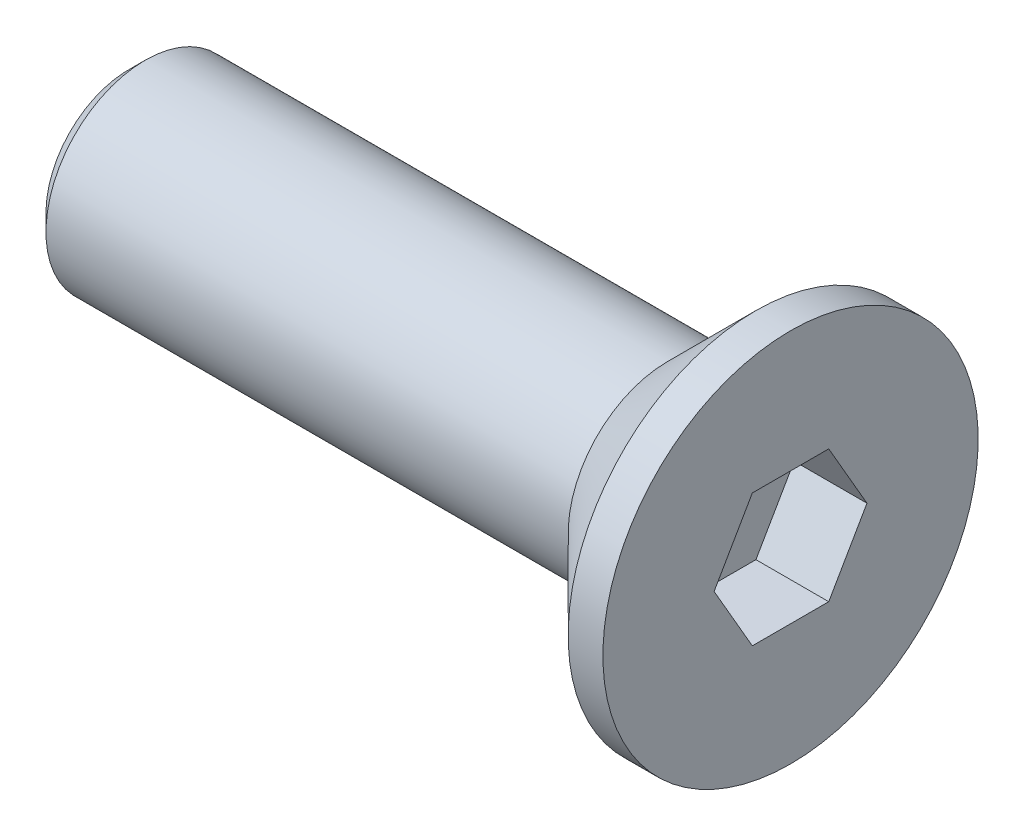
SolidWorks part; units mm, degrees
material "AISI 1020"
ref_plane "Front Plane" through (0, 0, 0) normal (0, 0, 1) x (1, 0, 0)
ref_plane "Top Plane" through (0, 0, 0) normal (0, 1, 0) x (1, 0, 0)
ref_plane "Right Plane" through (0, 0, 0) normal (1, 0, 0) x (0, 0, -1)
sketch "Sketch1" plane through (0, 0, 0) normal (0, 0, 1) x (1, 0, 0)
  line L0 (0, 0) -> (-20, 0) construction
  line L1 (0, 0) -> (0, 5.67)
  line L2 (0, 5.67) -> (-1.05, 5.67)
  line L3 (-1.05, 5.67) -> (-3.72, 3)
  line L4 (-3.72, 3) -> (-20, 3)
  line L5 (-20, 3) -> (-20, 0)
  line L6 (-20, 0) -> (0, 0)
  dimension "Diam" = 6
  dimension "Ilgis" = 20
  dimension "D3" = 45
  dimension "G_diam" = 11.34
  dimension "G_plotis" = 3.72
revolve "Revolve1" add sketch "Sketch1" angle 360 about L0
cosmetic thread "Cosmetic Thread1" parameters "Sr_ilgis"=16.28, "Sr_diam"=5
sketch "Sketch2" plane through (0, 0, 0) normal (1, 0, 0) x (0, 0, -1)
  line L1 (2.3094, 0) -> (1.1547, 2)
  line L2 (1.1547, 2) -> (-1.1547, 2)
  line L3 (-1.1547, 2) -> (-2.3094, 0)
  line L4 (-2.3094, 0) -> (-1.1547, -2)
  line L5 (-1.1547, -2) -> (1.1547, -2)
  line L6 (1.1547, -2) -> (2.3094, 0)
  circle A0 centre (0, 0) radius 2 construction
  dimension "R_plotis" = 4
extrude "Cut-Extrude1" cut sketch "Sketch2" against normal blind 2.2
chamfer "Chamfer1" distance 0.5 angle 45 1 edges at (-20, 3, 0)
